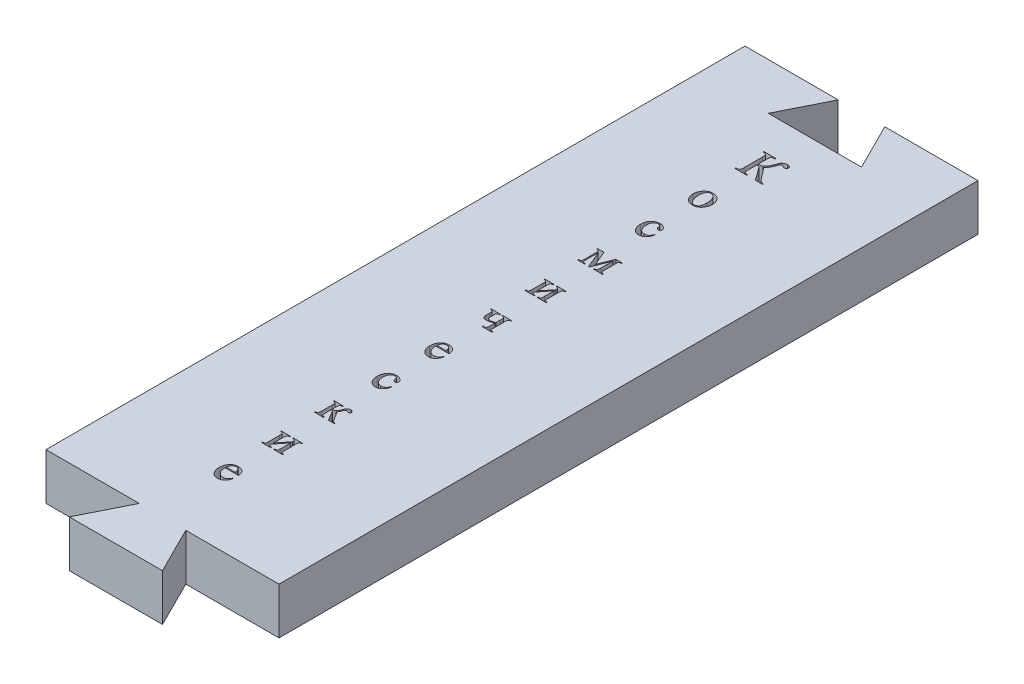
SolidWorks part; units mm, degrees
ref_plane "Спереди" through (0, 0, 0) normal (0, 0, 1) x (1, 0, 0)
ref_plane "Сверху" through (0, 0, 0) normal (0, 1, 0) x (1, 0, 0)
ref_plane "Справа" through (0, 0, 0) normal (1, 0, 0) x (0, 0, -1)
sketch "Эскиз1" plane through (0, 0, 0) normal (0, 1, 0) x (1, 0, 0)
  line L0 (10, 42.5) -> (2, 42.5)
  line L1 (10, -17.5) -> (2, -17.5)
  line L2 (10, -17.5) -> (10, 42.5)
  line L3 (-4, 38.5) -> (4, 38.5)
  line L4 (-10, -17.5) -> (-10, 42.5)
  line L5 (-4, -21.5) -> (4, -21.5)
  line L6 (4, -21.5) -> (2, -17.5)
  line L7 (-4, -21.5) -> (-2, -17.5)
  line L8 (-2, -17.5) -> (-10, -17.5)
  line L9 (4, 38.5) -> (2, 42.5)
  line L10 (-4, 38.5) -> (-2, 42.5)
  line L11 (-2, 42.5) -> (-10, 42.5)
  point P6 (-10, 42.5)
  dimension "D2" = 20
  dimension "D3" = 60
  dimension "D4" = 8
  dimension "D6" = 4
extrude "Бобышка-Вытянуть1" add sketch "Эскиз1" along normal blind 4 contours L4 L11 L10 L3 L9 L0 L2 L1 L6 L5 L7 L8
sketch "Эскиз2" plane through (0, 0, 0) normal (0, 1, 0) x (1, 0, 0)
  text T0 "К\r\nо\r\nс\r\nм\r\nи\r\nч\r\nе\r\nс\r\nк\r\nи\r\nе" font "Times New Roman" height 2.5
  point P1 (1.2875, 32.5286)
  point P2 (0, 0)
  point P3 (0, 0)
  point P4 (-1.3842, 32.9709)
extrude "Вырез-Вытянуть1" cut sketch "Эскиз2" along normal through all
